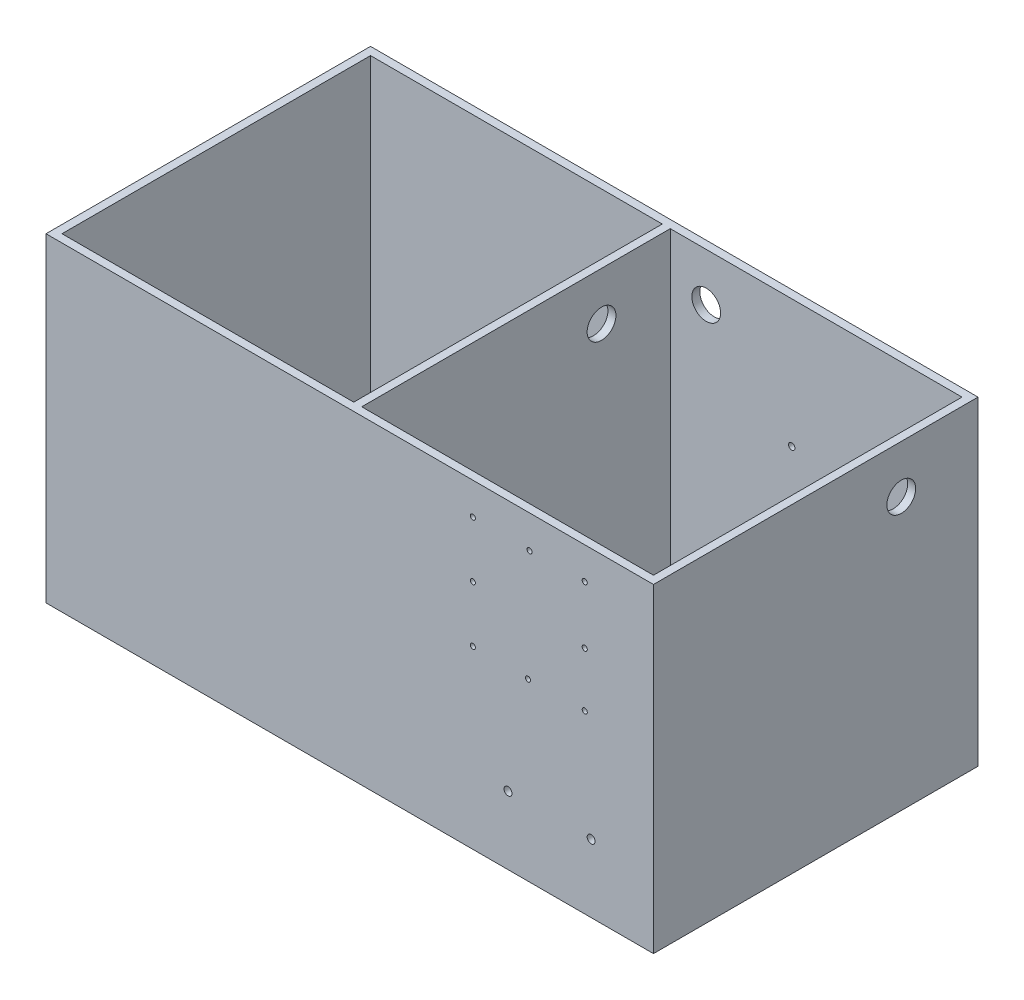
SolidWorks part; units mm, degrees
ref_plane "前视基准面" through (0, 0, 0) normal (0, 0, 1) x (1, 0, 0)
ref_plane "上视基准面" through (0, 0, 0) normal (0, 1, 0) x (1, 0, 0)
ref_plane "右视基准面" through (0, 0, 0) normal (1, 0, 0) x (0, 0, -1)
other "Configuration Table"
sketch "草图1" plane through (0, 0, 0) normal (0, 1, 0) x (1, 0, 0)
  line L0 (-190, 78.5) -> (-190, 101.5)
  line L1 (-167, 101.5) -> (167, 101.5)
  line L2 (-190, 78.5) -> (-190, -78.5)
  line L3 (-167, -101.5) -> (167, -101.5)
  line L4 (190, 78.5) -> (190, -78.5)
  line L5 (-190, 101.5) -> (190, -101.5) construction
  line L6 (-190, -101.5) -> (190, 101.5) construction
  line L7 (-190, 101.5) -> (-167, 101.5)
  line L8 (167, 101.5) -> (190, 101.5)
  line L9 (190, 101.5) -> (190, 78.5)
  line L10 (-190, -78.5) -> (-190, -101.5)
  line L11 (-190, -101.5) -> (-167, -101.5)
  line L12 (190, -78.5) -> (190, -101.5)
  line L13 (190, -101.5) -> (167, -101.5)
  point P0 (0, 0)
  dimension "D1" = 380
  dimension "D2" = 203
extrude "凸台-拉伸1" add sketch "草图1" along normal blind 200
sketch "草图3" plane through (0, 200, 0) normal (0, 1, 0) x (1, 0, 0)
  line L6 (-167, 96.5) -> (167, 96.5)
  line L8 (-185, 78.5) -> (-185, -78.5)
  line L9 (-167, -96.5) -> (167, -96.5)
  line L10 (185, 78.5) -> (185, -78.5)
  line L11 (-185, 96.5) -> (185, -96.5) construction
  line L12 (-185, -96.5) -> (185, 96.5) construction
  line L21 (-190, -101.5) -> (190, -101.5) construction
  line L22 (-190, 101.5) -> (-190, -101.5) construction
  line L23 (-185, 78.5) -> (-185, 96.5)
  line L24 (-185, 96.5) -> (-167, 96.5)
  line L25 (167, 96.5) -> (185, 96.5)
  line L26 (185, 96.5) -> (185, 78.5)
  line L27 (185, -78.5) -> (185, -96.5)
  line L28 (185, -96.5) -> (167, -96.5)
  line L29 (-185, -78.5) -> (-185, -96.5)
  line L30 (-185, -96.5) -> (-167, -96.5)
  point P0 (0, 0)
  point P1 (0, 0)
  dimension "D1" = 370
  dimension "D2" = 193
  dimension "D3" = 5
  dimension "D4" = 5
extrude "切除-拉伸1" cut sketch "草图3" against normal blind 195
sketch "草图9" plane through (190, 0, 0) normal (1, 0, 0) x (0, 0, -1)
  line L0 (-101.5, 200) -> (101.5, 200) construction
  line L2 (101.5, 200) -> (101.5, 0) construction
  circle A0 centre (53.5, 170) radius 9
  dimension "D1" = 18
  dimension "D2" = 30
  dimension "D3" = 48
extrude "切除-拉伸4" cut sketch "草图9" against normal up to next
sketch "草图11" plane through (0, 0, 101.5) normal (0, 0, 1) x (1, 0, 0)
  line L1 (77, 180) -> (147, 180) construction
  line L2 (77, 180) -> (77, 110) construction
  line L3 (77, 110) -> (147, 110) construction
  line L4 (147, 180) -> (147, 110) construction
  line L5 (77, 180) -> (147, 110) construction
  line L6 (77, 110) -> (147, 180) construction
  line L7 (-190, 200) -> (190, 200) construction
  line L8 (190, 200) -> (190, 0) construction
  circle A0 centre (77, 180) radius 1.6
  circle A1 centre (147, 180) radius 1.6
  circle A2 centre (77, 110) radius 1.6
  circle A3 centre (147, 110) radius 1.6
  point P0 (112, 145)
  dimension "D5" = 3.2
  dimension "D6" = 3.2
  dimension "D7" = 3.2
  dimension "D8" = 3.2
  dimension "D1" = 70
  dimension "D2" = 70
  dimension "D3" = 43
  dimension "D4" = 20
extrude "切除-拉伸5" cut sketch "草图11" against normal up to next
sketch "草图12" plane through (0, 0, 101.5) normal (0, 0, 1) x (1, 0, 0)
  line L0 (77, 180) -> (147, 110) construction
  line L1 (77, 180) -> (147, 180) construction
  line L2 (77, 180) -> (77, 110) construction
  line L3 (77, 110) -> (147, 110) construction
  line L4 (147, 180) -> (147, 110) construction
  line L5 (77, 110) -> (147, 180) construction
  circle A1 centre (77, 145) radius 1.6
  circle A2 centre (112.4964, 179.4965) radius 1.6
  circle A3 centre (146.9929, 144.0001) radius 1.6
  circle A4 centre (111.4965, 109.5036) radius 1.6
  point P2 (112, 145)
  point P17 (111.9964, 144.5001)
  dimension "D2" = 3.2
  dimension "D1" = 35
  dimension "D4" = 70
  dimension "D5" = 70
  dimension "D3" = 4
extrude "切除-拉伸6" cut sketch "草图12" against normal up to next
sketch "草图13" plane through (0, 0, 101.5) normal (0, 0, 1) x (1, 0, 0)
  line L0 (125, 71) -> (125, 14) construction
  line L5 (93, 71) -> (157, 71) construction
  line L6 (93, 71) -> (93, 14) construction
  line L7 (93, 14) -> (157, 14) construction
  line L8 (157, 71) -> (157, 14) construction
  line L9 (93, 42.5) -> (157, 42.5) construction
  line L11 (-190, 0) -> (190, 0) construction
  line L12 (190, 200) -> (190, 0) construction
  circle A0 centre (99, 42.5) radius 2.5
  circle A1 centre (151, 42.5) radius 2.5
  dimension "D3" = 5
  dimension "D1" = 64
  dimension "D2" = 57
  dimension "D4" = 26
  dimension "D6" = 52
  dimension "D8" = 14
  dimension "D7" = 33
  dimension "D5" = 2
extrude "切除-拉伸7" cut sketch "草图13" against normal up to next
sketch "草图14" plane through (0, 5, 0) normal (0, 1, 0) x (1, 0, 0)
  line L0 (-185, -96.5) -> (185, -96.5) construction
  line L3 (-2.5, 96.5) -> (2.5, 96.5)
  line L4 (-2.5, 96.5) -> (-2.5, -96.5)
  line L5 (-2.5, -96.5) -> (2.5, -96.5)
  line L6 (2.5, 96.5) -> (2.5, -96.5)
  line L7 (-2.5, 96.5) -> (2.5, -96.5) construction
  line L8 (-2.5, -96.5) -> (2.5, 96.5) construction
  point P0 (0, 0)
  dimension "D1" = 5
extrude "凸台-拉伸2" add sketch "草图14" along normal up to surface (195 mm away) up to face at (0, 200, 0)
sketch "草图15" plane through (0, 0, -101.5) normal (0, 0, -1) x (-1, 0, 0)
  line L0 (-190, 200) -> (190, 200) construction
  line L2 (0, 0) -> (0, 200) construction
  line L3 (-190, 200) -> (-190, 0) construction
  circle A0 centre (-155, 120) radius 2
  circle A1 centre (-78.5, 120) radius 2
  circle A2 centre (-78.5, 65) radius 2
  circle A3 centre (-155, 65) radius 2
  circle A4 centre (-25, 170) radius 9
  point P19 (-34.0663, 199)
  dimension "D1" = 4
  dimension "D7" = 18
  dimension "D2" = 80
  dimension "D3" = 35
  dimension "D6" = 30
  dimension "D8" = 25
  dimension "D4" = 2
  dimension "D5" = 2
extrude "切除-拉伸8" cut sketch "草图15" against normal up to next
sketch "草图16" plane through (2.5, 0, 0) normal (1, 0, 0) x (0, 0, -1)
  circle A1 centre (53.5, 170) radius 9
extrude "切除-拉伸9" cut sketch "草图16" against normal up to next
equation "\"D4@草图13\"=52/2MM"
